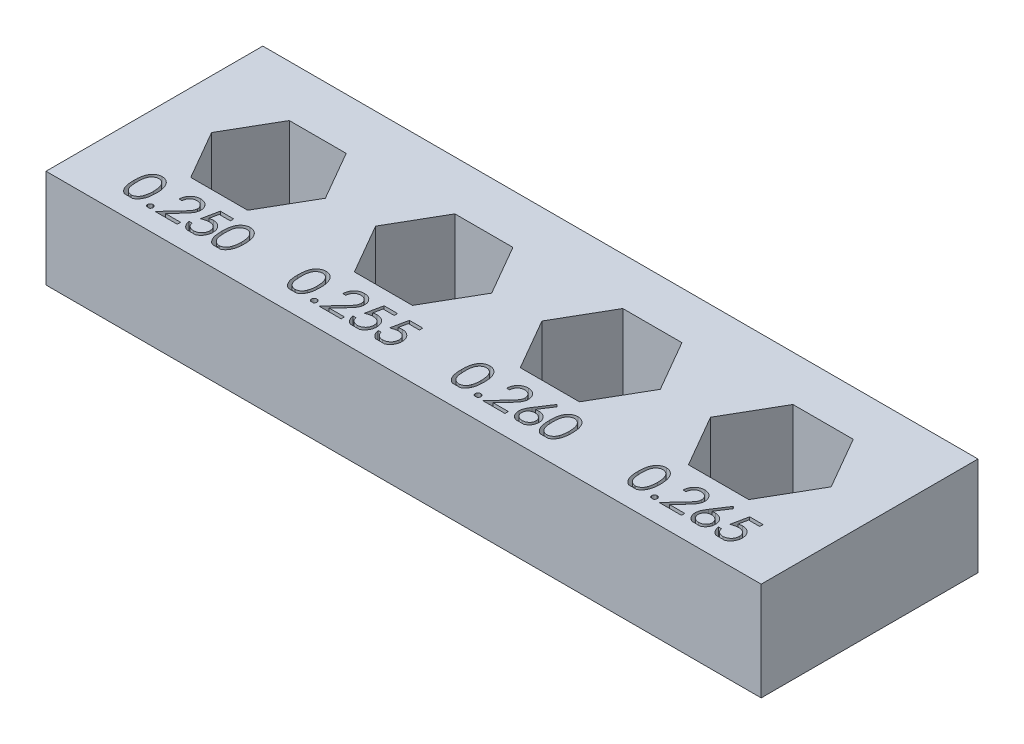
SolidWorks part; units mm, degrees
ref_plane "Front Plane" through (0, 0, 0) normal (0, 0, 1) x (1, 0, 0)
ref_plane "Top Plane" through (0, 0, 0) normal (0, 1, 0) x (1, 0, 0)
ref_plane "Right Plane" through (0, 0, 0) normal (1, 0, 0) x (0, 0, -1)
sketch "Sketch1" plane through (0, 0, 0) normal (0, 1, 0) x (1, 0, 0)
  line L11 (0, 0) -> (46.0843, 0)
  line L12 (0, 0) -> (0, 12.7)
  line L13 (0, 12.7) -> (46.0843, 12.7)
  line L14 (46.0843, 0) -> (46.0843, 12.7)
  line L32 (5.0081, 9.398) -> (8.6743, 9.398)
  line L33 (8.6743, 9.398) -> (10.5073, 6.223)
  line L34 (10.5073, 6.223) -> (8.6743, 3.048)
  line L35 (8.6743, 3.048) -> (5.0081, 3.048)
  line L36 (5.0081, 3.048) -> (3.175, 6.223)
  line L37 (3.175, 6.223) -> (5.0081, 9.398)
  line L38 (15.5521, 9.525) -> (19.2916, 9.525)
  line L39 (19.2916, 9.525) -> (21.1613, 6.2865)
  line L40 (21.1613, 6.2865) -> (19.2916, 3.048)
  line L41 (19.2916, 3.048) -> (15.5521, 3.048)
  line L42 (15.5521, 3.048) -> (13.6823, 6.2865)
  line L43 (13.6823, 6.2865) -> (15.5521, 9.525)
  line L62 (26.2428, 9.652) -> (30.0556, 9.652)
  line L63 (30.0556, 9.652) -> (31.962, 6.35)
  line L64 (31.962, 6.35) -> (30.0556, 3.048)
  line L65 (30.0556, 3.048) -> (26.2428, 3.048)
  line L66 (26.2428, 3.048) -> (24.3363, 6.35)
  line L67 (24.3363, 6.35) -> (26.2428, 9.652)
  line L68 (37.0801, 9.779) -> (40.9662, 9.779)
  line L69 (40.9662, 9.779) -> (42.9093, 6.4135)
  line L70 (42.9093, 6.4135) -> (40.9662, 3.048)
  line L71 (40.9662, 3.048) -> (37.0801, 3.048)
  line L72 (37.0801, 3.048) -> (35.137, 6.4135)
  line L73 (35.137, 6.4135) -> (37.0801, 9.779)
  point P0 (4.0915, 7.8105)
  point P1 (-192.984, 105.9899)
  point P2 (4.7346, 23.3597)
  point P3 (-191.4337, 107.3695)
  point P4 (0, 0)
  point P5 (-187.4427, 108.6998)
  point P6 (-190.2512, 114.3168)
  point P12 (-52.3181, 11.024)
  point P13 (0, 0)
  point P14 (-117.4709, 35.6505)
  point P15 (10.3422, 19.7341)
  point P16 (14.6172, 7.9058)
  point P23 (25.2895, 8.001)
  point P30 (36.1085, 8.0962)
  point P43 (0, 0)
  dimension "D1" = 6.35
  dimension "D2" = 6.35
  dimension "D4" = 6.35
  dimension "D7" = 6.477
  dimension "D8" = 6.477
  dimension "D9" = 6.477
  dimension "D13" = 6.604
  dimension "D14" = 6.604
  dimension "D15" = 6.604
  dimension "D19" = 6.731
  dimension "D20" = 6.731
  dimension "D21" = 6.731
  dimension "D25" = 3.175
  dimension "D26" = 3.175
  dimension "D27" = 0
  dimension "D28" = 120
  dimension "D29" = 120
  dimension "D30" = 120
  dimension "D31" = 120
  dimension "D32" = 3.175
  dimension "D33" = 0
  dimension "D34" = 3.175
  dimension "D35" = 0
  dimension "D36" = 12.7
  dimension "D37" = 3.175
  dimension "D38" = 3.175
extrude "Boss-Extrude2" add sketch "Sketch1" along normal blind 6.35
sketch "Sketch3" plane through (0, 6.35, 0) normal (0, 1, 0) x (1, 0, 0)
  text T0 "    0.250    0.255    0.260     0.265" font "Century Gothic" height in points 8
extrude "Cut-Extrude1" cut sketch "Sketch3" against normal blind 3.175
sketch "Sketch4" plane through (0, 6.35, 0) normal (0, 1, 0) x (1, 0, 0)
  line L1 (46.0843, 0) -> (0, 0)
  line L2 (46.0843, 0) -> (46.0843, -1.27)
  line L3 (46.0843, -1.27) -> (0, -1.27)
  line L4 (0, 0) -> (0, -1.27)
  dimension "D1" = 1.27
extrude "Boss-Extrude3" add sketch "Sketch4" against normal blind 6.35
equation "\"a\"= 0.25"
equation "\"D1@Sketch1\"=\"a\""
equation "\"D2@Sketch1\"=\"a\""
equation "\"D4@Sketch1\"=\"a\""
equation "\"b\"= 0.255"
equation "\"D9@Sketch1\"=\"b\""
equation "\"D7@Sketch1\"=\"b\""
equation "\"D8@Sketch1\"=\"b\""
equation "\"c\"=0.26"
equation "\"D13@Sketch1\"=\"c\""
equation "\"D14@Sketch1\"=\"c\""
equation "\"D15@Sketch1\"=\"c\""
equation "\"d\"=0.265"
equation "\"D19@Sketch1\"=\"d\""
equation "\"D20@Sketch1\"=\"d\""
equation "\"D21@Sketch1\"=\"d\""
